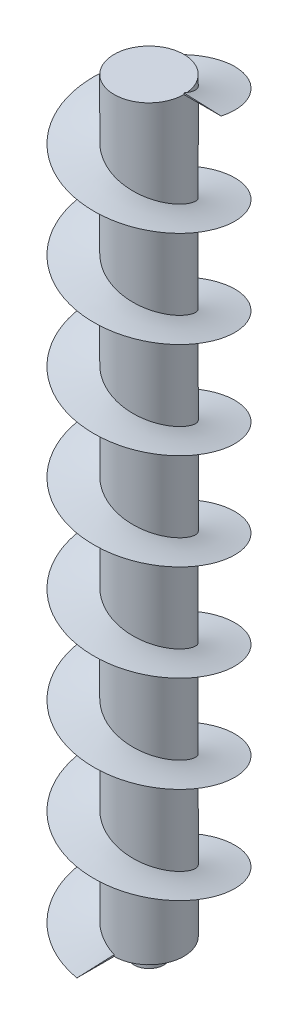
SolidWorks part; units mm, degrees
ref_plane "前基準面" through (0, 0, 0) normal (0, 0, 1) x (1, 0, 0)
ref_plane "上基準面" through (0, 0, 0) normal (0, 1, 0) x (1, 0, 0)
ref_plane "右基準面" through (0, 0, 0) normal (1, 0, 0) x (0, 0, -1)
sketch "草圖1" plane through (0, 0, 0) normal (0, 1, 0) x (1, 0, 0)
  circle A0 centre (0, 0) radius 7
  dimension "D1" = 14
extrude "填料-伸長1" add sketch "草圖1" along normal blind 150 contours A0
sketch "草圖2" plane through (0, 0, 0) normal (0, -1, 0) x (1, 0, 0)
  circle A1 centre (0, 0) radius 7
  circle A2 centre (0, 0) radius 7
  dimension "D1" = 0
curve "螺旋曲線/渦捲線1" pitch 19.3548 height 150 turns 7.75
sketch "草圖4" plane through (0, 0, 0) normal (1, 0, 0) x (0, 0, -1)
  line L0 (-7, 0.3) -> (-14.5, 0)
  line L1 (-7, 0) -> (-14.5, 0)
  line L2 (-7, 0) -> (-7, 0.3)
  dimension "D1" = 0.3
  dimension "D2" = 7.5
sweep "掃出2" add profiles "草圖4" path "螺旋曲線/渦捲線1"
sketch "草圖8" plane through (0, 0, 0) normal (0, -1, 0) x (1, 0, 0)
  circle A0 centre (0, 0) radius 3
  dimension "D1" = 6
extrude "填料-伸長2" add sketch "草圖8" along normal blind 5
sketch "草圖9" plane through (0, -5, 0) normal (0, -1, 0) x (1, 0, 0)
  circle A1 centre (0, 0) radius 3
  circle A2 centre (0, 0) radius 3
  dimension "D1" = 0
extrude "除料-伸長1" cut sketch "草圖9" against normal blind 1.5
